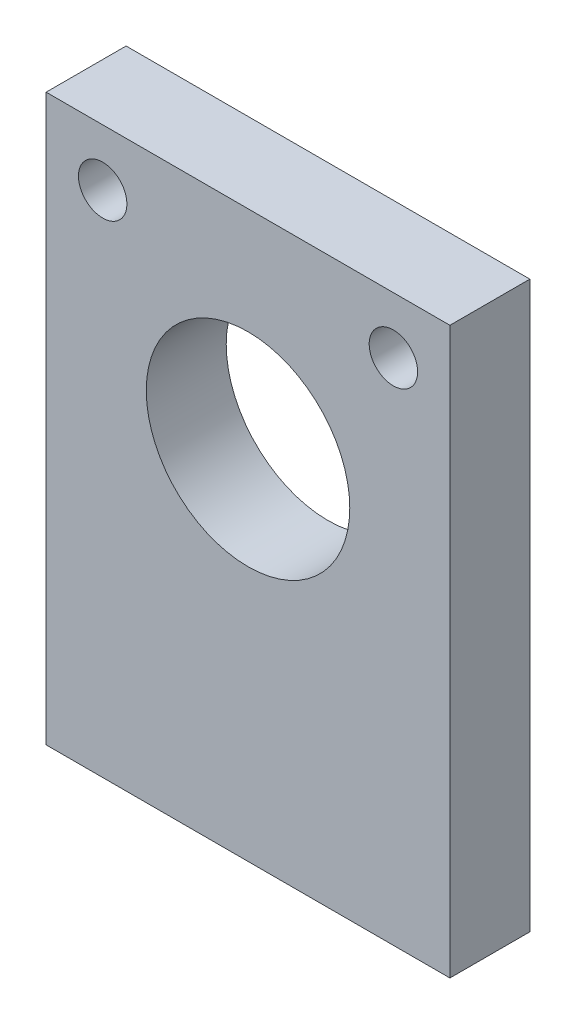
SolidWorks part; units mm, degrees
ref_plane "Alzado" through (0, 0, 0) normal (0, 0, 1) x (1, 0, 0)
ref_plane "Planta" through (0, 0, 0) normal (0, 1, 0) x (1, 0, 0)
ref_plane "Vista lateral" through (0, 0, 0) normal (1, 0, 0) x (0, 0, -1)
sketch "Croquis1" plane through (0, 0, 0) normal (0, 0, 1) x (1, 0, 0)
  line L1 (-25, 35) -> (25, 35)
  line L2 (-25, 35) -> (-25, -35)
  line L3 (-25, -35) -> (25, -35)
  line L4 (25, 35) -> (25, -35)
  line L5 (-25, 35) -> (25, -35) construction
  line L6 (-25, -35) -> (25, 35) construction
  circle A0 centre (-18, 28) radius 3
  circle A1 centre (18, 28) radius 3
  point P0 (0, 0)
  dimension "D1" = 70
  dimension "D2" = 50
extrude "Saliente-Extruir1" add sketch "Croquis1" along normal blind 9.9
sketch "Croquis2" plane through (0, 0, 9.9) normal (0, 0, 1) x (1, 0, 0)
  circle A0 centre (0, 9.2098) radius 12.6
  dimension "D1" = 25.2
extrude "Cortar-Extruir1" cut sketch "Croquis2" against normal blind 9.9
